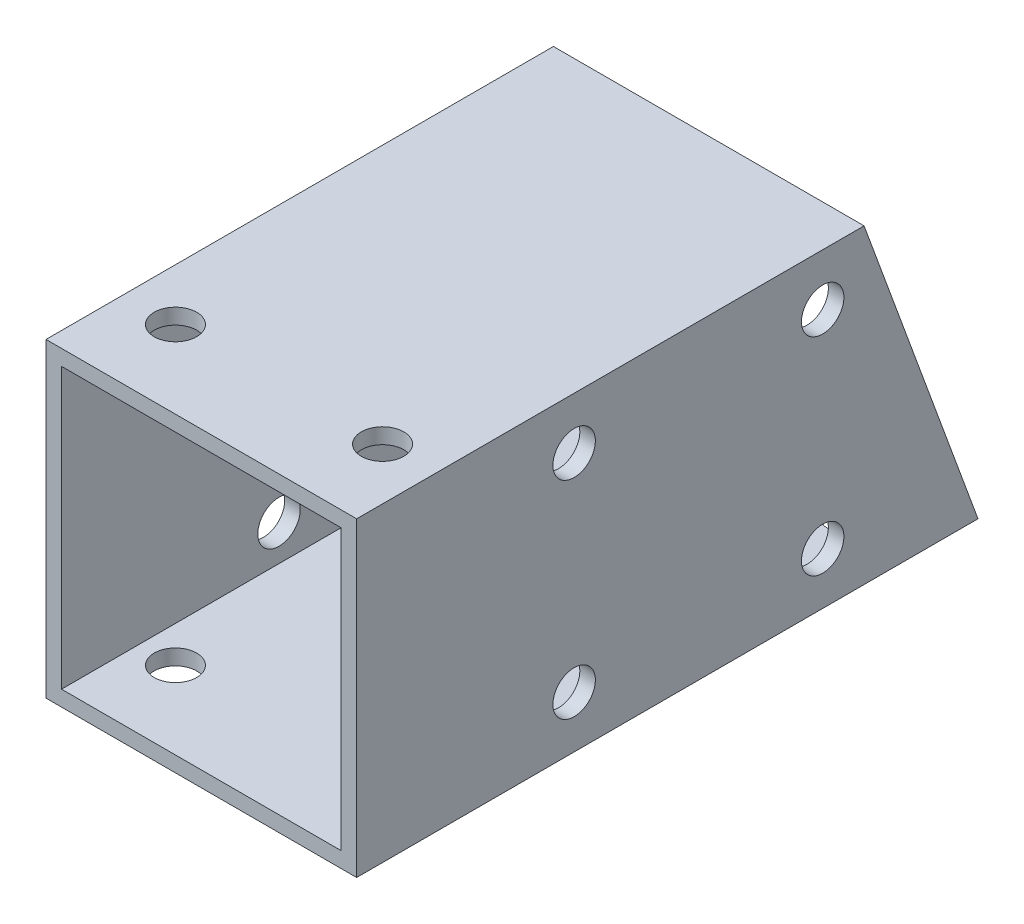
SolidWorks part; units mm, degrees
material "6061 合金"
ref_plane "前视基准面" through (0, 0, 0) normal (0, 0, 1) x (1, 0, 0)
ref_plane "上视基准面" through (0, 0, 0) normal (0, 1, 0) x (1, 0, 0)
ref_plane "右视基准面" through (0, 0, 0) normal (1, 0, 0) x (0, 0, -1)
other "Configuration Table"
sketch "草图1" plane through (0, 0, 0) normal (0, 0, 1) x (1, 0, 0)
  line L0 (-13.5, 13.5) -> (-13.5, -13.5)
  line L1 (-15, 15) -> (15, 15)
  line L2 (-15, 15) -> (-15, -15)
  line L3 (-15, -15) -> (15, -15)
  line L4 (15, 15) -> (15, -15)
  line L5 (-15, 15) -> (15, -15) construction
  line L6 (-15, -15) -> (15, 15) construction
  line L7 (-13.5, -13.5) -> (13.5, -13.5)
  line L8 (13.5, 13.5) -> (13.5, -13.5)
  line L9 (-13.5, 13.5) -> (13.5, 13.5)
  point P0 (0, 0)
  dimension "D1" = 30
  dimension "D2" = 30
  dimension "D3" = 1.5
extrude "凸台-拉伸1" add sketch "草图1" along normal blind 60
sketch "草图2" plane through (0, 15, 0) normal (0, 1, 0) x (1, 0, 0)
  line L0 (-15, -30) -> (15, -30) construction
  line L1 (-15, -60) -> (-15, 0) construction
  line L2 (15, -60) -> (15, 0) construction
  line L3 (0, 0) -> (0, -60) construction
  line L4 (15, -60) -> (-15, -60) construction
  line L6 (-10, -7.5) -> (10, -7.5) construction
  line L7 (-10, -7.5) -> (-10, -52.5) construction
  line L8 (-10, -52.5) -> (10, -52.5) construction
  line L9 (10, -7.5) -> (10, -52.5) construction
  line L10 (-10, -7.5) -> (10, -52.5) construction
  line L11 (-10, -52.5) -> (10, -7.5) construction
  circle A0 centre (-10, -7.5) radius 2.05
  circle A1 centre (10, -7.5) radius 2.05
  circle A2 centre (-10, -52.5) radius 2.05
  circle A3 centre (10, -52.5) radius 2.05
  point P11 (0, -30)
  dimension "D3" = 4.1
  dimension "D1" = 20
  dimension "D2" = 45
extrude "切除-拉伸1" cut sketch "草图2" against normal through all
sketch "草图3" plane through (15, 0, 0) normal (1, 0, 0) x (0, 0, -1)
  line L0 (0, 13.5) -> (0, -13.5) construction
  line L1 (-39, 10) -> (-15, 10) construction
  line L2 (-39, 10) -> (-39, -10) construction
  line L3 (-39, -10) -> (-15, -10) construction
  line L4 (-15, 10) -> (-15, -10) construction
  line L5 (-39, 10) -> (-15, -10) construction
  line L6 (-39, -10) -> (-15, 10) construction
  line L7 (-60, -15) -> (0, -15) construction
  circle A0 centre (-39, 10) radius 2.05
  circle A1 centre (-39, -10) radius 2.05
  circle A2 centre (-15, -10) radius 2.05
  circle A3 centre (-15, 10) radius 2.05
  point P0 (-27, 0)
  dimension "D5" = 4.1
  dimension "D1" = 20
  dimension "D2" = 24
  dimension "D3" = 27
  dimension "D4" = 5
extrude "切除-拉伸2" cut sketch "草图3" against normal through all
sketch "草图4" plane through (15, 0, 0) normal (1, 0, 0) x (0, 0, -1)
  line L0 (-60, -15) -> (-49, 15)
  line L1 (-60, 15) -> (0, 15) construction
  line L2 (-49, 15) -> (-60, 15)
  line L3 (-1005.5, 15) -> (-5.5, 15) construction
  line L4 (-105.5, 15) -> (-55.5, 15) construction
  line L5 (-60, 15) -> (-60, -15)
  dimension "D1" = 11
sketch "草图5" plane through (15, 0, 0) normal (1, 0, 0) x (0, 0, -1)
  line L0 (0, -15) -> (-11, 15)
  line L1 (-11, 15) -> (0, 15)
  line L2 (0, 15) -> (0, -15)
  dimension "D1" = 11
extrude "切除-拉伸4" cut sketch "草图5" against normal through all
